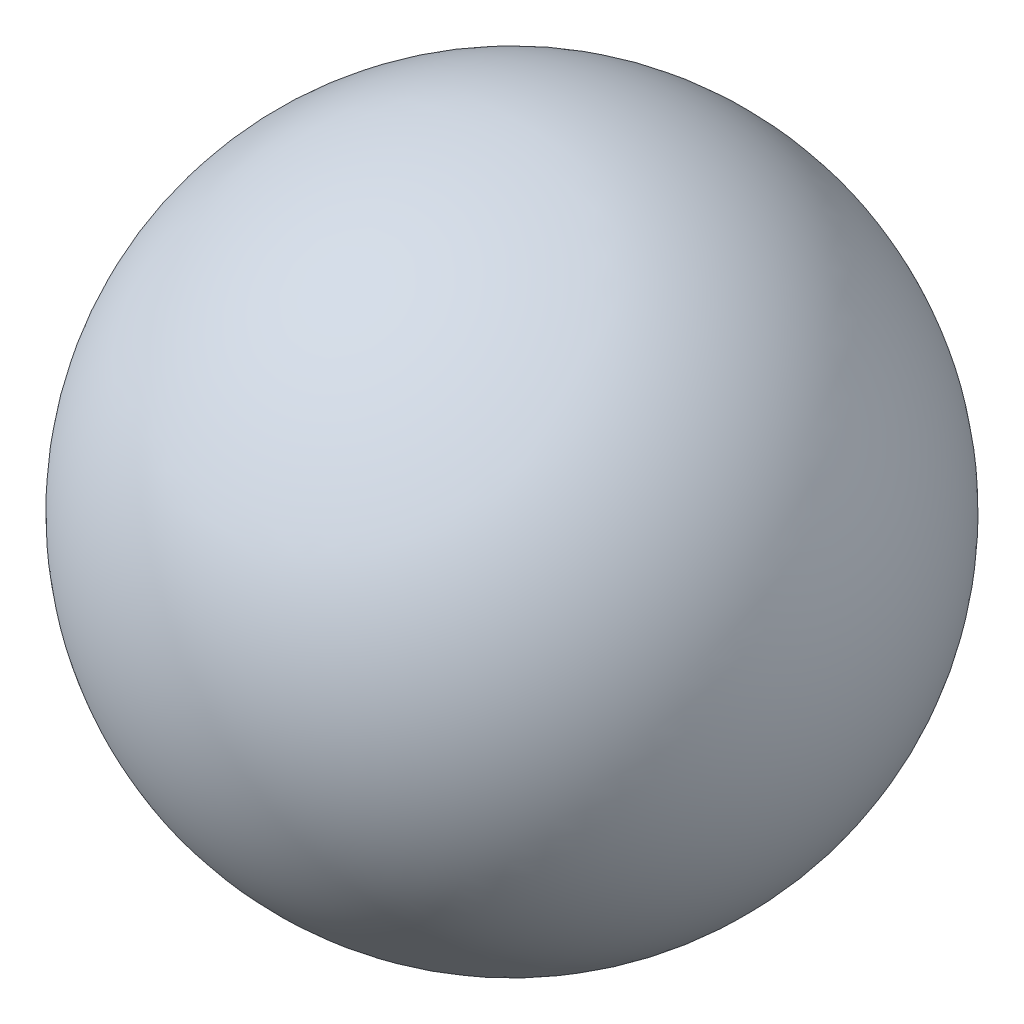
SolidWorks part; units mm, degrees
ref_plane "Front" through (0, 0, 0) normal (0, 0, 1) x (1, 0, 0)
ref_plane "Top" through (0, 0, 0) normal (0, 1, 0) x (1, 0, 0)
ref_plane "Right" through (0, 0, 0) normal (1, 0, 0) x (0, 0, -1)
sketch "Sketch1" plane through (0, 0, 0) normal (0, 1, 0) x (1, 0, 0)
  line L0 (0, 0) -> (0, 21.335) construction
  line L1 (0, 0) -> (0, -21.335) construction
  line L2 (0, 21.335) -> (0, -21.335)
  arc A0 (0, 21.335) -> (0, -21.335) centre (0, 0) ccw
  dimension "D1" = 42.67
revolve "Revolve5" add sketch "Sketch1" angle 360 about L2
